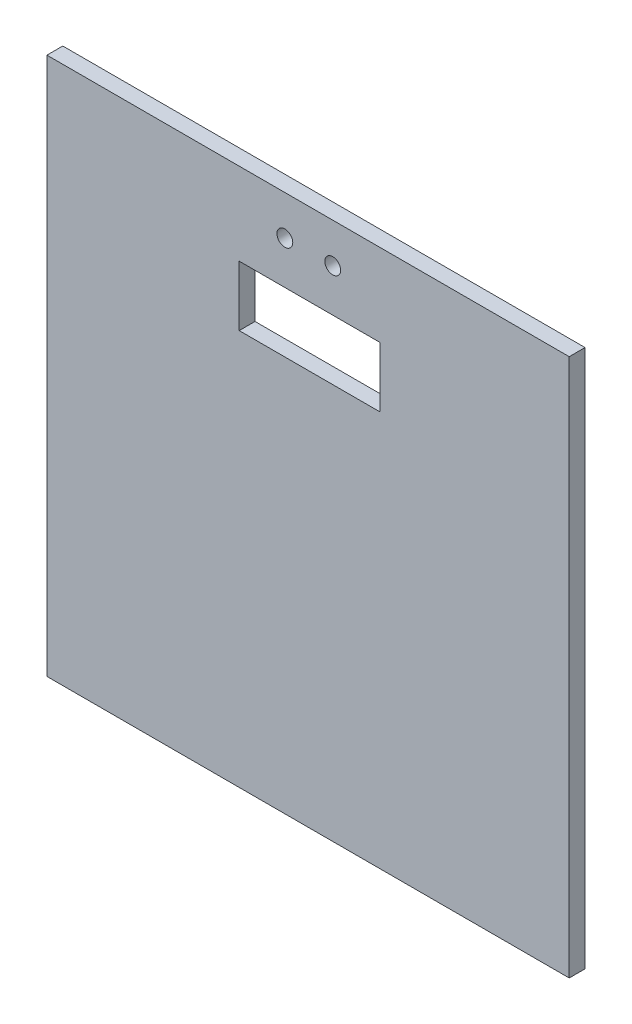
SolidWorks part; units mm, degrees
ref_plane "Front Plane" through (0, 0, 0) normal (0, 0, 1) x (1, 0, 0)
ref_plane "Top Plane" through (0, 0, 0) normal (0, 1, 0) x (1, 0, 0)
ref_plane "Right Plane" through (0, 0, 0) normal (1, 0, 0) x (0, 0, -1)
other "Graphic1"
other "object_1 (Open) -1"
ref_plane "Plane1" through (0, 0, 30) normal (0, 0, 1) x (1, 0, 0)
sketch "Sketch1" plane through (0, 0, 30) normal (0, 0, 1) x (1, 0, 0)
  line L1 (218.9409, 335.024) -> (284.9409, 335.024)
  line L2 (218.9409, 335.024) -> (218.9409, 267.024)
  line L3 (218.9409, 267.024) -> (284.9409, 267.024)
  line L4 (284.9409, 335.024) -> (284.9409, 267.024)
  line L5 (243.235, 324.6239) -> (261.035, 324.6239)
  line L6 (243.235, 324.6239) -> (243.235, 317.0239)
  line L7 (243.235, 317.0239) -> (261.035, 317.0239)
  line L8 (261.035, 324.6239) -> (261.035, 317.0239)
  circle A0 centre (249.0036, 330.0315) radius 1
  circle A1 centre (255.0553, 330.0315) radius 1
  dimension "D3" = 17.8
  dimension "D1" = 66
  dimension "D2" = 68
  dimension "D4" = 7.6
extrude "Boss-Extrude1" add sketch "Sketch1" along normal blind 2
